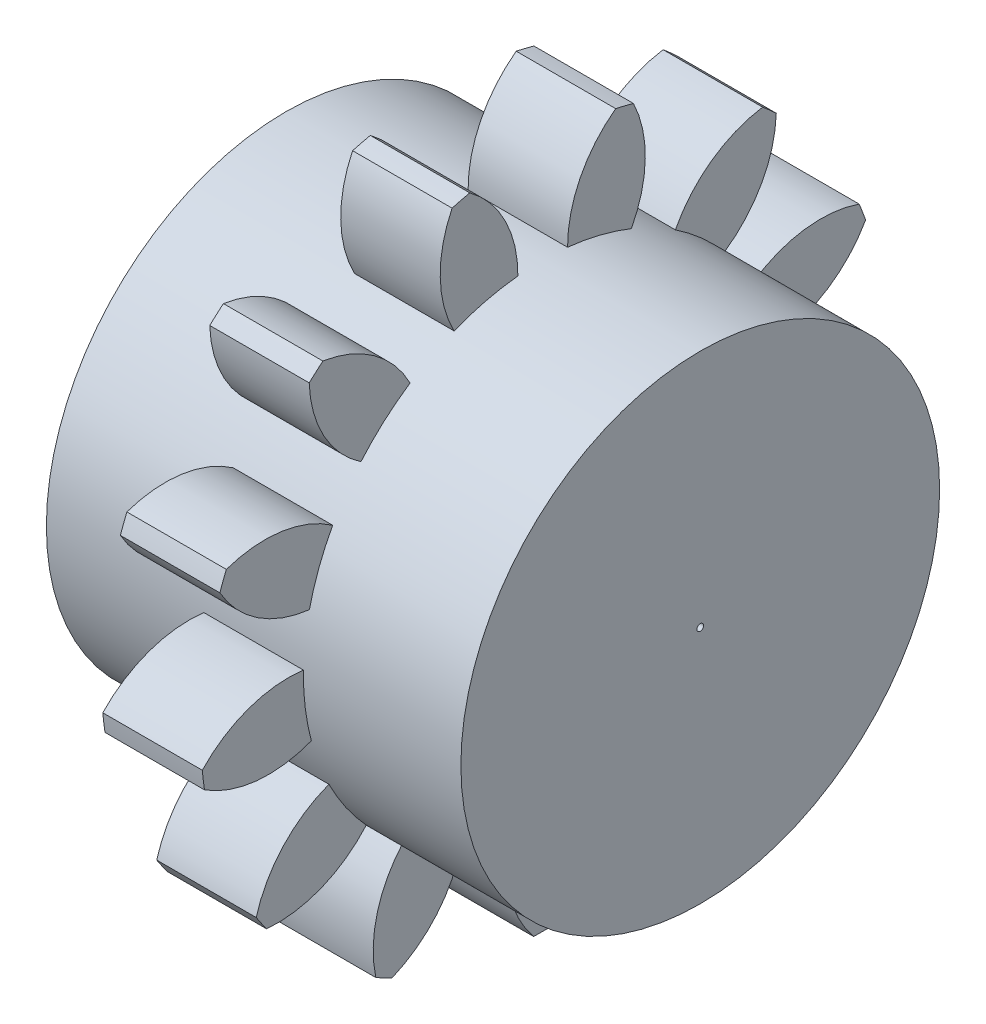
SolidWorks part; units mm, degrees
ref_plane "Plane1" through (0, 0, 0) normal (0, 0, 1) x (1, 0, 0)
ref_plane "Plane2" through (0, 0, 0) normal (0, 1, 0) x (1, 0, 0)
ref_plane "Plane3" through (0, 0, 0) normal (1, 0, 0) x (0, 0, -1)
sketch "HoldingSke" plane through (0, 0, 0) normal (0, 1, 0) x (1, 0, 0)
  line L0 (0, 0) -> (0.1772, -0.0409)
  line L1 (-15, 0) -> (100, 0) construction
  line L2 (0, 0) -> (-2.1039, 2.3779)
  line L3 (0, 0) -> (-11.863, 4.5341)
  line L4 (0, 0) -> (8.4147, 1.9427)
  line L5 (0, 0) -> (-46.8476, -17.4728)
  line L6 (0, 0) -> (-9.9476, -6.7116)
  line L7 (-2.1039, 2.3779) -> (8.6586, 51.2059)
  line L8 (-76.2, 54.61) -> (-76.1, 54.61)
  line L9 (-71.009, 38.7566) -> (-53.1078, 45.2721)
  line L10 (-76.2, 71.12) -> (104.1128, 71.12)
  line L11 (0, 0) -> (-12, 0)
  line L12 (-76.2, 101.6) -> (-76.013, 101.6)
  line L13 (24.9733, 27.94) -> (52.9518, 28.4284)
  line L14 (24.9733, 27.94) -> (24.9743, 27.94)
  line L15 (24.9733, 27.94) -> (100.4006, 29.5858)
  line L16 (-63.627, -5.5) -> (-12.827, -5.5)
  circle A0 centre (0, 0) radius 0.4
  circle A1 centre (0, 0) radius 28.874
  circle A2 centre (0, 0) radius 37.5
  circle A3 centre (0, 0) radius 0.4
  dimension "Bore" = 0.8
  dimension "MBD" = 0.8
  dimension "Num_teeth" = 13
  dimension "Show_teeth" = 13
  dimension "T_dim" = 0.1
  dimension "Ap" = 20
  dimension "H" = 19.05
  dimension "Pitch_radius" = 180.3128
  dimension "Addendum_fac" = 1
  dimension "Dedendum_fac" = 1.25
  dimension "Clearance_fac" = 0.25
  dimension "Dedendum_add" = 0.001
sketch "BasProSke" plane through (0, 0, 0) normal (0, 1, 0) x (1, 0, 0)
  line L0 (-10, 0) -> (60, 0) construction
  line L1 (0, 0) -> (0, 41.25)
  line L2 (0, 0) -> (12, 0)
  line L3 (12, 0) -> (12, 41.25)
  line L4 (12, 41.25) -> (0, 41.25)
revolve "Base-Revolve" add sketch "BasProSke" angle 360 about L0
sketch "TooCutSke" plane through (0, 0, 0) normal (1, 0, 0) x (0, 0, -1)
  line L1 (0, 0) -> (0, 107) construction
  line L2 (0, 0) -> (-4.6361, 35.4481) construction
  line L3 (0, 0) -> (-17.0046, 68.9904) construction
  line L4 (-4.6361, 35.4481) -> (-8.5023, 34.4952) construction
  arc A0 (2.9966, 28.7181) -> (-2.9966, 28.7181) centre (0, 0) ccw
  arc A1 (8.8261, 40.3207) -> (-8.8261, 40.3207) centre (0, 0) ccw
  circle A2 centre (0, 0) radius 35.75 construction
  circle A3 centre (0, 0) radius 33.594 construction
  arc A4 (-2.9966, 28.7181) -> (-8.8261, 40.3207) centre (-17.2963, 28.7992) ccw
  arc A5 (8.8261, 40.3207) -> (2.9966, 28.7181) centre (17.2963, 28.7992) ccw
  dimension "Half_ang" = 13.846
extrude "ToothCut" cut sketch "TooCutSke" along normal through all
fillet "Breaks" [suppressed] radius 0.11
fillet "RootFillets" [suppressed] radius 1.376
pattern_circular "TeethCuts" count 13 every 27.692 about axis through (-10, 0, 0) along (1, 0, 0) of "ToothCut", "RootFillets", "Breaks"
sketch "HubNeaOneSke" plane through (0, 0, 0) normal (-1, 0, 0) x (0, 0, 1)
  circle A0 centre (0, 0) radius 28.874
extrude "HubNearOne" [suppressed] add sketch "HubNeaOneSke" along normal blind 38.0001
sketch "HubNeaBotSke" plane through (0, 0, 0) normal (-1, 0, 0) x (0, 0, 1)
  circle A0 centre (0, 0) radius 28.874
extrude "HubNearBoth" add sketch "HubNeaBotSke" along normal blind 19
ref_plane "FarPln" through (12, 0, 0) normal (1, 0, 0) x (0, 0, -1)
sketch "HubFarSke" plane through (12, 0, 0) normal (1, 0, 0) x (0, 0, -1)
  circle A0 centre (0, 0) radius 28.874
extrude "HubFar" add sketch "HubFarSke" along normal blind 19
sketch "BorSke" plane through (0, 0, 0) normal (1, 0, 0) x (0, 0, -1)
  circle A0 centre (0, 0) radius 0.4
  dimension "Diameter" = 0.8
extrude "Bore" cut sketch "BorSke" along normal mid plane 100.0001
sketch "KeySke" plane through (0, 0, 0) normal (1, 0, 0) x (0, 0, -1)
  line L0 (-0.05, 0) -> (-0.05, 0.5)
  line L1 (-0.05, 0.5) -> (0.05, 0.5)
  line L2 (0.05, 0.5) -> (0.05, 0)
  line L3 (0, 0) -> (0, 34) construction
  line L4 (-0.05, 0) -> (0.05, 0)
  dimension "Offset" = 0.5
  dimension "Width" = 0.1
extrude "Keyway" [suppressed] cut sketch "KeySke" along normal mid plane 100.0001
pattern_circular "Keyway2" [suppressed] count 2 every 90 about axis through (-10, 0, 0) along (1, 0, 0)
equation "' \"Module@HoldingSke\" = 6.35"
equation "' \"Num_teeth@HoldingSke\" = 12"
equation "' \"Ap@HoldingSke\" =  20"
equation "' \"Ap@HoldingSke\" = 20"
equation "' \"Width@HoldingSke\" = 0.5 * 25.4"
equation "' \"Hub_dia@HoldingSke\"= 1 * 25.4"
equation "' \"Hub_dia@HoldingSke\" = 1 * 25.4"
equation "' \"Overall_len@HoldingSke\" = 1.0 * 25.4"
equation "' \"Bore@HoldingSke\" = 0.75 * 25.4"
equation "' \"T_dim@HoldingSke\" = 0.1 * 25.4"
equation "' \"Width@KeySke\" = 0.25 * 25.4"
equation "' \"Show_teeth@HoldingSke\" = 13"
equation "' \"Backlash@HoldingSke\" = 0.009 * 25.4"
equation "' \"Addendum_fac@HoldingSke\" = 1.0"
equation "' \"Dedendum_fac@HoldingSke\" = 1.25"
equation "' \"Dedendum_add@HoldingSke\" = 0.00005 * 25.4"
equation "' \"Clearance_fac@HoldingSke\" = 0.25"
equation "\"Pitch@HoldingSke\" = 1 / \"Module@HoldingSke\""
equation "\"Overcut_dia@TooCutSke\" = (\"Num_teeth@HoldingSke\" + 2 * \"Addendum_fac@HoldingSke\") / \"Pitch@HoldingSke\" + 0.002 * 25.4"
equation "\"Pitch_dia@TooCutSke\" = \"Num_teeth@HoldingSke\" / \"Pitch@HoldingSke\""
equation "\"Base_dia@TooCutSke\" = \"Num_teeth@HoldingSke\" / \"Pitch@HoldingSke\" * cos((\"Ap@HoldingSke\"  * 3.14159265 / 180))"
equation "\"Root_dia@TooCutSke\" = (\"Num_teeth@HoldingSke\" + 2) / \"Pitch@HoldingSke\" - 2 * (\"Addendum_fac@HoldingSke\" + \"Dedendum_fac@HoldingSke\") / \"Pitch@HoldingSke\" - \"Dedendum_add@HoldingSke\" * 2"
equation "\"Half_ang@TooCutSke\" = 180 / \"Num_teeth@HoldingSke\""
equation "\"Half_CT@TooCutSke\" = \"Num_teeth@HoldingSke\" / \"Pitch@HoldingSke\" * sin((3.14159265 / 2 / \"Num_teeth@HoldingSke\")) / 2 - 7 * \"Backlash@HoldingSke\" / 4"
equation "\"Flank_rad@TooCutSke\" = \"Num_teeth@HoldingSke\" / \"Pitch@HoldingSke\" / 5"
equation "\"Radius@RootFillets\" = \"Clearance_fac@HoldingSke\" / \"Pitch@HoldingSke\" + \"Dedendum_add@HoldingSke\""
equation "\"Break_rad@Breaks\" = 0.02 / \"Pitch@HoldingSke\""
equation "\"Thickness@HoldingSke\" = \"Width@HoldingSke\""
equation "\"OAL@HoldingSke\" = \"Thickness@HoldingSke\""
equation "\"MHD@HoldingSke\" = (\"Num_teeth@HoldingSke\" + 2) / \"Pitch@HoldingSke\" - 2 * (\"Addendum_fac@HoldingSke\" + \"Dedendum_fac@HoldingSke\")  / \"Pitch@HoldingSke\" - \"Dedendum_add@HoldingSke\" * 2"
equation "\"MBD@HoldingSke\" = (\"Num_teeth@HoldingSke\" + 2) / \"Pitch@HoldingSke\" - 2 * (\"Addendum_fac@HoldingSke\" + \"Dedendum_fac@HoldingSke\")  / \"Pitch@HoldingSke\" - \"Dedendum_add@HoldingSke\" * 2 - 0.002 * 25.4"
equation "\"MHD@HoldingSke\" = ((sgn( \"MHD@HoldingSke\" - \"Hub_dia@HoldingSke\" )-1)*( \"MHD@HoldingSke\" - \"Hub_dia@HoldingSke\" ))/-2+ \"Hub_dia@HoldingSke\""
equation "\"MBD@HoldingSke\" = ((sgn( \"MBD@HoldingSke\" - \"Bore@HoldingSke\" )-1)*( \"MBD@HoldingSke\" - \"Bore@HoldingSke\" ))/-2+ \"Bore@HoldingSke\""
equation "\"OAL@HoldingSke\" = ((sgn( \"OAL@HoldingSke\" - \"Overall_len@HoldingSke\" )+1)*( \"OAL@HoldingSke\" - \"Overall_len@HoldingSke\" ))/2 + \"Overall_len@HoldingSke\" + 0.000002 * 25.4"
equation "\"Num_teeth@TeethCuts\" = int( \"Show_teeth@HoldingSke\" ) + 1"
equation "\"Num_teeth@TeethCuts\" = ((sgn( \"Num_teeth@TeethCuts\" - \"Num_teeth@HoldingSke\" )-1)*( \"Num_teeth@TeethCuts\" - \"Num_teeth@HoldingSke\" ))/-2+ \"Num_teeth@HoldingSke\""
equation "\"Num_teeth@TeethCuts\" = ((sgn( \"Num_teeth@TeethCuts\" - 2.0)+1)*( \"Num_teeth@TeethCuts\" - 2.0))/2 +2.0"
equation "\"Angle@TeethCuts\" = 360.0 / \"Num_teeth@HoldingSke\""
equation "\"Diameter@BasProSke\" = (\"Num_teeth@HoldingSke\" + 2 * \"Addendum_fac@HoldingSke\") / \"Pitch@HoldingSke\""
equation "\"Thickness@BasProSke\"  = \"Thickness@HoldingSke\""
equation "' \"Fillet_rad@BasProSke\" =  \"Thickness@HoldingSke\" * 0.05"
equation "' \"Fillet_rad@BasProSke\" = \"Thickness@HoldingSke\" * 0.05"
equation "\"MHD@HoldingSke\" = ((sgn( \"MHD@HoldingSke\" - \"Root_dia@TooCutSke\" )-1)*( \"MHD@HoldingSke\" - \"Root_dia@TooCutSke\" ))/-2+ \"Root_dia@TooCutSke\""
equation "\"Diameter@HubNeaOneSke\" = \"MHD@HoldingSke\""
equation "\"Length@HubNearOne\" = \"OAL@HoldingSke\" - \"Thickness@BasProSke\""
equation "\"Diameter@HubNeaBotSke\" = \"MHD@HoldingSke\""
equation "\"Length@HubNearBoth\" = ( \"OAL@HoldingSke\" - \"Thickness@BasProSke\" ) / 2.0"
equation "\"Thickness@FarPln\" = \"Thickness@BasProSke\""
equation "\"Diameter@HubFarSke\" = \"MHD@HoldingSke\""
equation "\"Length@HubFar\" = ( \"OAL@HoldingSke\" - \"Thickness@BasProSke\" ) / 2.0"
equation "\"Diameter@BorSke\" = \"MBD@HoldingSke\""
equation "\"D1@Bore\" = \"OAL@HoldingSke\" * 2.0"
equation "\"D1@Keyway\" = \"OAL@HoldingSke\" * 2.0"
equation "\"Offset@KeySke\" = \"T_dim@HoldingSke\" + \"MBD@HoldingSke\" / 2.0"
